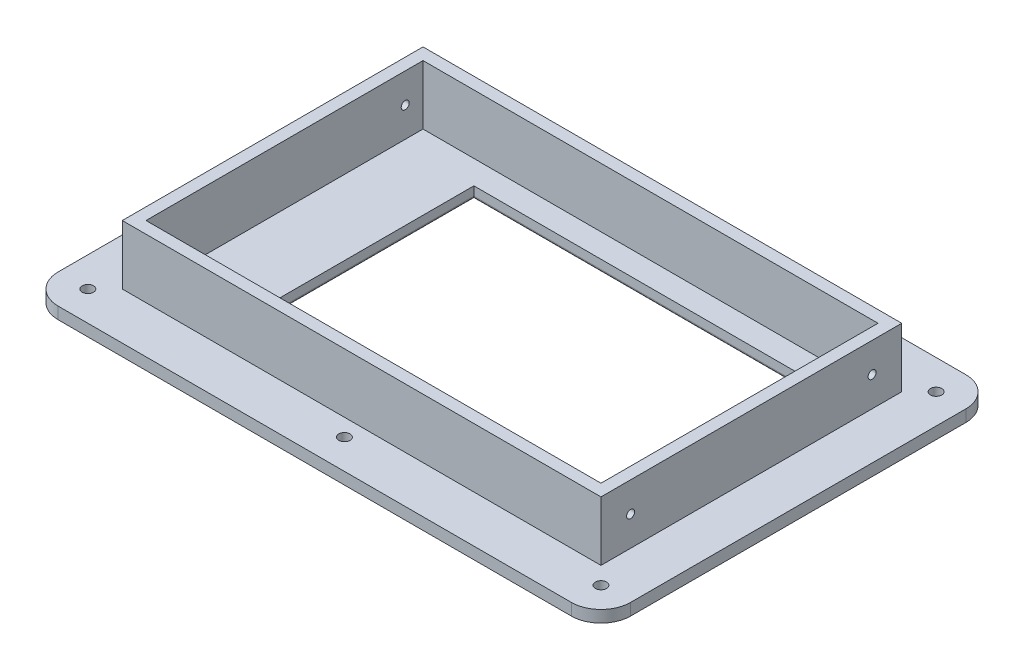
SolidWorks part; units mm, degrees
ref_plane "Front Plane" through (0, 0, 0) normal (0, 0, 1) x (1, 0, 0)
ref_plane "Top Plane" through (0, 0, 0) normal (0, 1, 0) x (1, 0, 0)
ref_plane "Right Plane" through (0, 0, 0) normal (1, 0, 0) x (0, 0, -1)
sketch "Sketch1" plane through (0, 0, 0) normal (0, 1, 0) x (1, 0, 0)
  line L1 (-96.5, -66.5) -> (96.5, -66.5)
  line L2 (-96.5, -66.5) -> (-96.5, 66.5)
  line L3 (-96.5, 66.5) -> (96.5, 66.5)
  line L4 (96.5, -66.5) -> (96.5, 66.5)
  line L5 (-96.5, -66.5) -> (96.5, 66.5) construction
  line L6 (-96.5, 66.5) -> (96.5, -66.5) construction
  point P0 (0, 0)
  dimension "D1" = 133
  dimension "D2" = 193
extrude "Boss-Extrude1" add sketch "Sketch1" along normal blind 4
sketch "Sketch2" plane through (0, 4, 0) normal (0, 1, 0) x (1, 0, 0)
  line L1 (-76.7, -46.7) -> (76.7, -46.7)
  line L2 (-76.7, -46.7) -> (-76.7, 46.7)
  line L3 (-76.7, 46.7) -> (76.7, 46.7)
  line L4 (76.7, -46.7) -> (76.7, 46.7)
  line L5 (-76.7, -46.7) -> (76.7, 46.7) construction
  line L6 (-76.7, 46.7) -> (76.7, -46.7) construction
  point P0 (0, 0)
  dimension "D1" = 93.4
  dimension "D2" = 153.4
extrude "Extrude-Thin1" add sketch "Sketch2" along normal blind 20 thin
sketch "Sketch3" plane through (0, 0, 0) normal (0, -1, 0) x (1, 0, 0)
  line L0 (76.7, 46.7) -> (76.7, -46.7) construction
  line L1 (60.45, 32.2) -> (-51.55, 32.2)
  line L2 (60.45, 32.2) -> (60.45, -38.7)
  line L3 (60.45, -38.7) -> (-51.55, -38.7)
  line L4 (-51.55, 32.2) -> (-51.55, -38.7)
  line L5 (4.45, -38.7) -> (4.45, 32.2) construction
  line L6 (60.45, -3.25) -> (-51.55, -3.25) construction
  line L7 (-76.7, 46.7) -> (76.7, 46.7) construction
  line L8 (76.7, -46.7) -> (-76.7, -46.7) construction
  line L10 (-96.5, -66.5) -> (-96.5, 66.5) construction
  line L11 (96.5, 66.5) -> (96.5, -66.5) construction
  point P512 (4.45, -3.25)
  dimension "D1" = 16.25
  dimension "D2" = 14.5
  dimension "D3" = 8
  dimension "D4" = 112
  dimension "D5" = 44.95
  dimension "D6" = 36.05
  dimension "D7" = 70.9
extrude "Cut-Extrude3" cut sketch "Sketch3" against normal blind 15
fillet "Fillet1" radius 1 4 edges at (4.45, 0, -38.7) (60.45, 0, -3.25) (-51.55, 0, -3.25) (4.45, 0, 32.2)
hole_wizard "#25 (0.1495) Diameter Hole2" positions "Sketch6" profile "Sketch5" hole size "#25" standard "ANSI Inch" end condition through all
sketch "Sketch6" plane through (0, 0, 0) normal (0, -1, 0) x (-1, 0, 0)
  line L0 (96.5, 66.5) -> (96.5, -66.5) construction
  line L1 (96.5, -66.5) -> (-96.5, -66.5) construction
  line L2 (-96.5, 66.5) -> (96.5, 66.5) construction
  line L3 (-96.5, -66.5) -> (-96.5, 66.5) construction
  point P0 (86.5, -56.5)
  point P2 (86.5, 56.5)
  point P4 (-86.5, 56.5)
  point P6 (-86.5, -56.5)
  point P17 (0, -56.5)
  point P19 (0, 56.5)
  dimension "D1" = 10
  dimension "D2" = 10
  dimension "D3" = 10
  dimension "D4" = 10
  dimension "D5" = 10
  dimension "D6" = 10
  dimension "D7" = 10
  dimension "D8" = 10
sketch "Sketch5" plane through (-86.5, 0, 56.5) normal (1, 0, 0) x (0, 0, -1)
  line L0 (0, 0) -> (0, 24)
  line L1 (0, 24) -> (1.8986, 24)
  line L2 (1.8986, 24) -> (1.8986, 0)
  line L5 (1.8986, 0) -> (0, 0)
  line L11 (0, -6.35) -> (0, 107.95) construction
  dimension "Thru Hole Dia." = 3.7973
  dimension "Thru Hole Depth" = 24
fillet "Fillet3" radius 10 4 edges at (96.5, 2, -66.5) (96.5, 2, 66.5) (-96.5, 2, 66.5) (-96.5, 2, -66.5)
hole_wizard "Tap Drill for #6-32 Tap1" positions "Sketch9" profile "Sketch10" hole size "#6-32" standard "ANSI Inch" end condition through all
sketch "Sketch9" plane through (-80.7, 0, 0) normal (-1, 0, 0) x (0, 0, 1)
  line L0 (-50.7, 24) -> (50.7, 24) construction
  line L1 (-50.7, 24) -> (-50.7, 4) construction
  line L2 (50.7, 24) -> (50.7, 4) construction
  point P0 (-40.7, 14)
  point P2 (40.7, 14)
  dimension "D1" = 10
  dimension "D2" = 10
  dimension "D3" = 10
sketch "Sketch10" plane through (-80.7, 14, -40.7) normal (0, 1, 0) x (0, 0, 1)
  line L0 (0, 0) -> (0, 177.2)
  line L1 (0, 177.2) -> (1.3525, 177.2)
  line L2 (1.3525, 177.2) -> (1.3525, 0)
  line L5 (1.3525, 0) -> (0, 0)
  line L11 (0, -6.35) -> (0, 107.95) construction
  dimension "Thru Hole Dia." = 2.7051
  dimension "Thru Hole Depth" = 177.2
